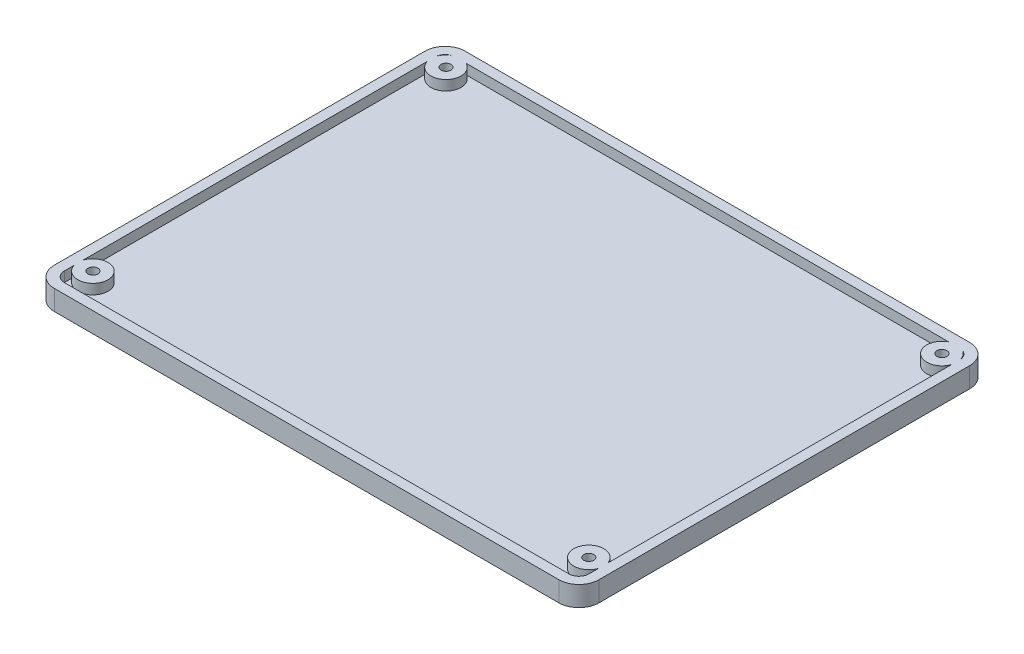
SolidWorks part; units mm, degrees
ref_plane "Front Plane" through (0, 0, 0) normal (0, 0, 1) x (1, 0, 0)
ref_plane "Top Plane" through (0, 0, 0) normal (0, 1, 0) x (1, 0, 0)
ref_plane "Right Plane" through (0, 0, 0) normal (1, 0, 0) x (0, 0, -1)
sketch "Sketch1" plane through (0, 0, 0) normal (0, 1, 0) x (1, 0, 0)
  line L1 (-81.4, 61.4) -> (81.4, 61.4)
  line L2 (-81.4, 61.4) -> (-81.4, -61.4)
  line L3 (-81.4, -61.4) -> (81.4, -61.4)
  line L4 (81.4, 61.4) -> (81.4, -61.4)
  line L5 (-81.4, 61.4) -> (81.4, -61.4) construction
  line L6 (-81.4, -61.4) -> (81.4, 61.4) construction
  circle A0 centre (-74.1002, 54.367) radius 1.5
  circle A1 centre (74.1074, 54.367) radius 1.5
  circle A2 centre (74.1074, -51.1504) radius 1.5
  circle A3 centre (-74.1002, -51.1504) radius 1.5
  point P0 (0, 0)
  dimension "D3" = 3
  dimension "D6" = 7.2926
  dimension "D7" = 7.2926
  dimension "D1" = 162.8
  dimension "D2" = 122.8
  dimension "D4" = 2
  dimension "D5" = 2
extrude "Boss-Extrude1" add sketch "Sketch1" along normal blind 6
fillet "Fillet1" radius 6 4 edges at (81.4, 3, -61.4) (-81.4, 3, -61.4) (-81.4, 3, 61.4) (81.4, 3, 61.4)
shell "Shell5" thickness 3
